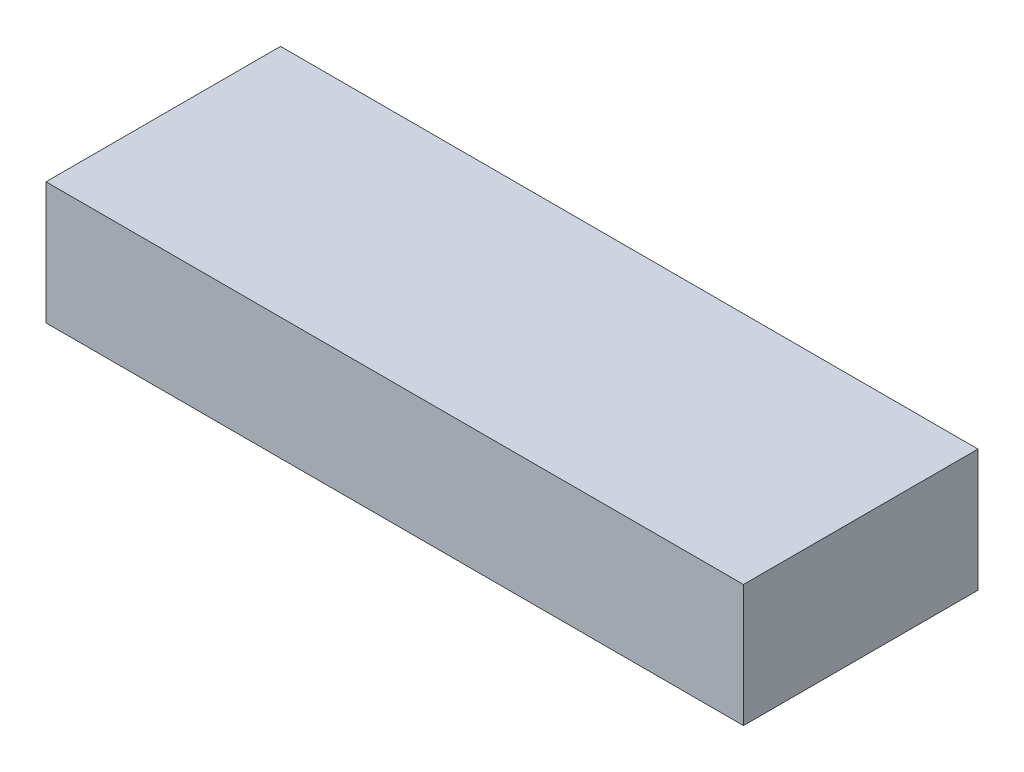
SolidWorks part; units mm, degrees
ref_plane "Спереди" through (0, 0, 0) normal (0, 0, 1) x (1, 0, 0)
ref_plane "Сверху" through (0, 0, 0) normal (0, 1, 0) x (1, 0, 0)
ref_plane "Справа" through (0, 0, 0) normal (1, 0, 0) x (0, 0, -1)
sketch "Sketch1" plane through (0, 0, 0) normal (0, 1, 0) x (1, 0, 0)
  line L18 (0, 0) -> (57.0597, 0)
  line L19 (0, 0) -> (0, 19.1863)
  line L20 (0, 19.1863) -> (57.0597, 19.1863)
  line L21 (57.0597, 0) -> (57.0597, 19.1863)
  point P3 (56.3931, 19.1863)
  point P4 (55.6831, 0)
  point P5 (57.0597, 0)
extrude "Boss-Extrude1" add sketch "Sketch1" along normal blind 10 contours L21 L20 L19 L18
